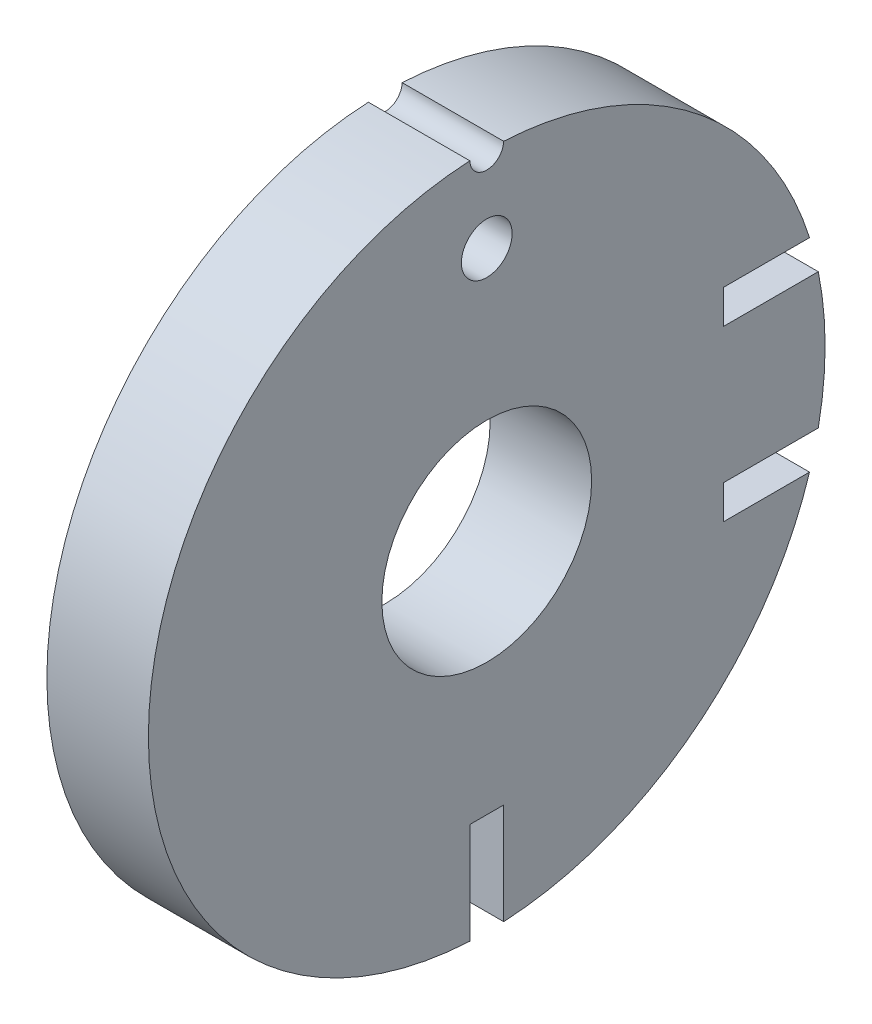
SolidWorks part; units mm, degrees
ref_plane "Front Plane" through (0, 0, 0) normal (0, 0, 1) x (1, 0, 0)
ref_plane "Top Plane" through (0, 0, 0) normal (0, 1, 0) x (1, 0, 0)
ref_plane "Right Plane" through (0, 0, 0) normal (1, 0, 0) x (0, 0, -1)
sketch "Sketch1" plane through (0, 0, 0) normal (1, 0, 0) x (0, 0, -1)
  circle A0 centre (0, 0) radius 10
  circle A1 centre (0, 0) radius 3.1
  dimension "D1" = 6.2
  dimension "D2" = 20
extrude "Boss-Extrude1" add sketch "Sketch1" along normal blind 3
sketch "Sketch2" plane through (3, 0, 0) normal (1, 0, 0) x (0, 0, -1)
  line L1 (7, 3) -> (12.7097, 3)
  line L2 (7, 3) -> (7, 2)
  line L3 (7, 2) -> (12.7097, 2)
  line L4 (12.7097, 3) -> (12.7097, 2)
  line L5 (7, -2) -> (12.7097, -2)
  line L6 (7, -2) -> (7, -3)
  line L7 (7, -3) -> (12.7097, -3)
  line L8 (12.7097, -2) -> (12.7097, -3)
  line L9 (-0.5, -7) -> (0.5, -7)
  line L10 (-0.5, -7) -> (-0.5, -11.5058)
  line L11 (-0.5, -11.5058) -> (0.5, -11.5058)
  line L12 (0.5, -7) -> (0.5, -11.5058)
  circle A0 centre (0, 7.5) radius 0.75
  circle A1 centre (0, 0) radius 10 construction
  circle A2 centre (0, 10) radius 0.5
  dimension "D1" = 1.5
  dimension "D3" = 1
  dimension "D12" = 0.5
  dimension "D2" = 7.5
  dimension "D4" = 1
  dimension "D5" = 1
  dimension "D6" = 1
  dimension "D7" = 7
  dimension "D8" = 7
  dimension "D9" = 7
  dimension "D10" = 2
  dimension "D11" = 2
extrude "Cut-Extrude1" cut sketch "Sketch2" against normal blind 3
